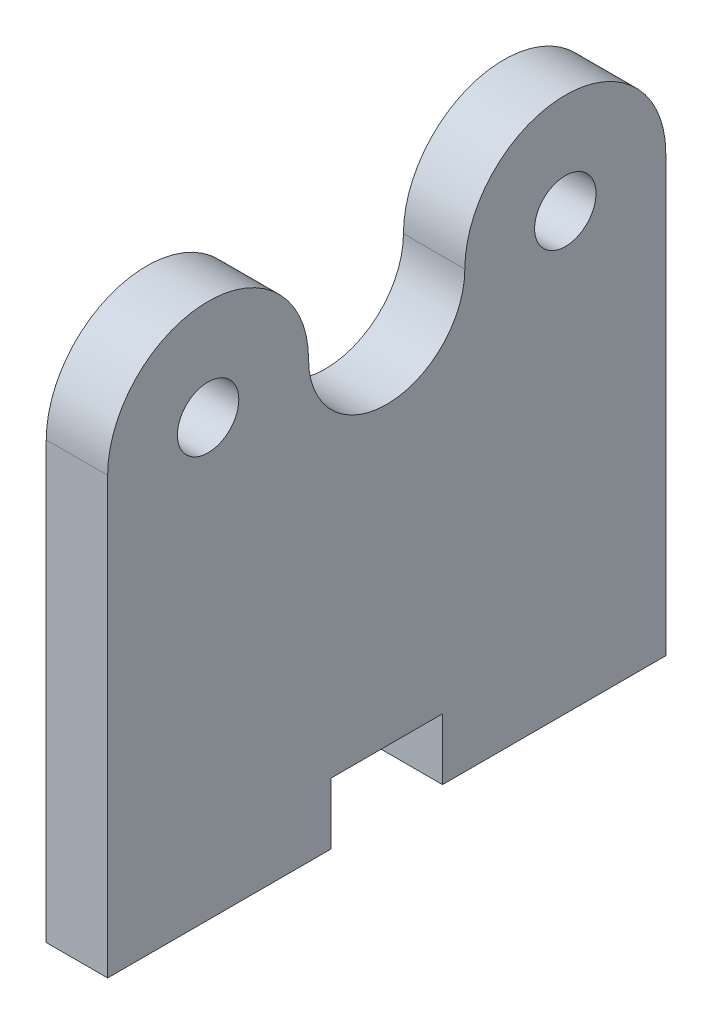
SolidWorks part; units mm, degrees
ref_plane "Alzado" through (0, 0, 0) normal (0, 0, 1) x (1, 0, 0)
ref_plane "Planta" through (0, 0, 0) normal (0, 1, 0) x (1, 0, 0)
ref_plane "Vista lateral" through (0, 0, 0) normal (1, 0, 0) x (0, 0, -1)
sketch "Croquis1" plane through (0, 0, 0) normal (1, 0, 0) x (0, 0, -1)
  line L0 (-25, 0) -> (-25, -33.5)
  line L1 (-5, -33.5) -> (5, -33.5)
  line L2 (25, -33.5) -> (25, 0)
  line L3 (-25, -33.5) -> (-25, -39)
  line L4 (-25, -39) -> (-5, -39)
  line L5 (-5, -39) -> (-5, -33.5)
  line L6 (25, -33.5) -> (25, -39)
  line L7 (25, -39) -> (5, -39)
  line L8 (5, -39) -> (5, -33.5)
  arc A0 (25, 0) -> (7, 0) centre (16, 0) ccw
  circle A1 centre (-16, 0) radius 2.75
  circle A2 centre (16, 0) radius 2.75
  arc A4 (-7, 0) -> (-25, 0) centre (-16, 0) ccw
  arc A5 (-7, 0) -> (7, 0) centre (0, 0) ccw
  dimension "D1" = 7
  dimension "D2" = 16
  dimension "D3" = 16
  dimension "D4" = 5.5
  dimension "D5" = 5.5
  dimension "D8" = 25
  dimension "D9" = 5.5
  dimension "D6" = 33.5
  dimension "D7" = 25
  dimension "D10" = 20
  dimension "D11" = 10
extrude "Saliente-Extruir1" add sketch "Croquis1" along normal blind 5.5
